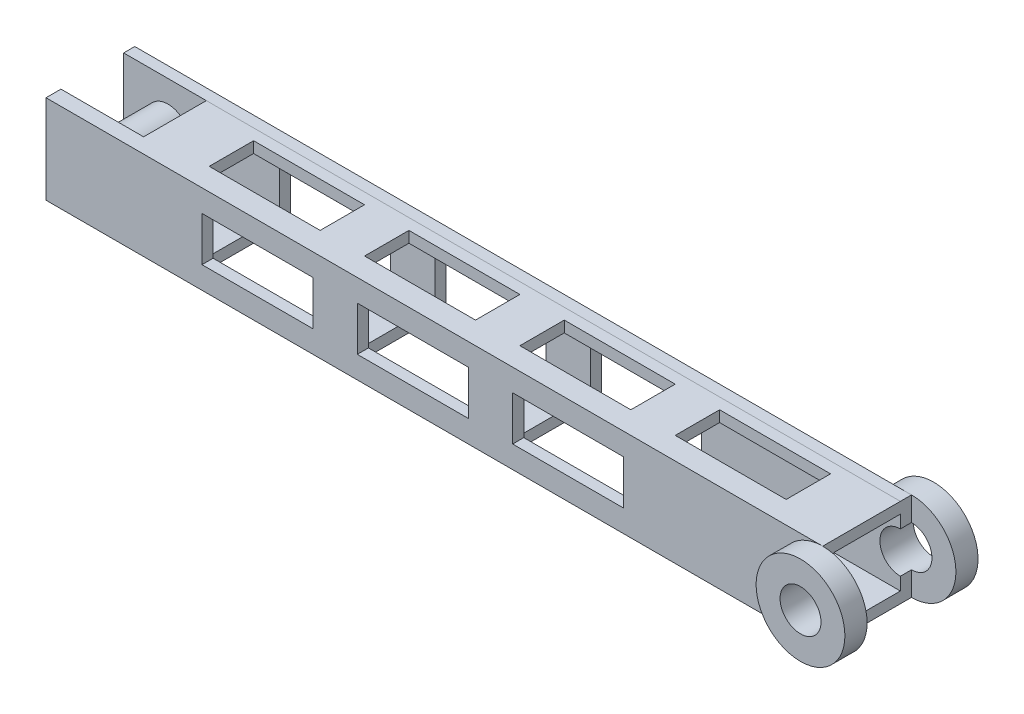
SolidWorks part; units mm, degrees
material "ENPH 253 Hardboard"
ref_plane "Front Plane" through (0, 0, 0) normal (0, 0, 1) x (1, 0, 0)
ref_plane "Top Plane" through (0, 0, 0) normal (0, 1, 0) x (1, 0, 0)
ref_plane "Right Plane" through (0, 0, 0) normal (1, 0, 0) x (0, 0, -1)
sketch "Sketch1" plane through (0, 0, 0) normal (0, 0, 1) x (1, 0, 0)
  line L1 (-109.1179, 29.5837) -> (240.8821, 29.5837)
  line L2 (-109.1179, 29.5837) -> (-109.1179, -10.4163)
  line L3 (-109.1179, -10.4163) -> (240.8821, -10.4163)
  line L4 (240.8821, 29.5837) -> (240.8821, -10.4163)
  dimension "D1" = 350
  dimension "D2" = 40
extrude "Boss-Extrude1" add sketch "Sketch1" along normal blind 5
sketch "Sketch2" plane through (0, 0, 5) normal (0, 0, 1) x (1, 0, 0)
  line L0 (-109.1179, 29.5837) -> (-109.1179, -10.4163) construction
  line L1 (-109.1179, 29.5849) -> (240.8821, 29.5849)
  line L2 (-109.1179, 29.5849) -> (-109.1179, 24.5849)
  line L3 (-109.1179, 24.5849) -> (240.8821, 24.5849)
  line L4 (240.8821, 29.5849) -> (240.8821, 24.5849)
  line L5 (240.8821, -10.4163) -> (240.8821, 29.5837) construction
  line L7 (-109.1179, -5.4163) -> (240.8821, -5.4163)
  line L8 (-109.1179, -5.4163) -> (-109.1179, -10.4163)
  line L9 (-109.1179, -10.4163) -> (240.8821, -10.4163)
  line L10 (240.8821, -5.4163) -> (240.8821, -10.4163)
  dimension "D1" = 5
  dimension "D2" = 5
extrude "Boss-Extrude2" add sketch "Sketch2" along normal blind 30 contours L2 L1 L4 L3
sketch "Sketch3" plane through (0, 0, 5) normal (0, 0, 1) x (1, 0, 0)
  line L0 (-109.1179, 24.5849) -> (-109.1179, -10.4163) construction
  line L1 (-109.1179, -5.4163) -> (240.8821, -5.4163)
  line L2 (-109.1179, -5.4163) -> (-109.1179, -10.4163)
  line L3 (-109.1179, -10.4163) -> (240.8821, -10.4163)
  line L4 (240.8821, -5.4163) -> (240.8821, -10.4163)
  dimension "D1" = 5
extrude "Boss-Extrude3" add sketch "Sketch3" along normal blind 30
sketch "Sketch5" plane through (0, 0, 35) normal (0, 0, 1) x (1, 0, 0)
  line L1 (-109.1179, 29.5849) -> (240.8821, 29.5849)
  line L2 (-109.1179, 29.5849) -> (-109.1179, -10.4163)
  line L3 (-109.1179, -10.4163) -> (240.8821, -10.4163)
  line L4 (240.8821, 29.5849) -> (240.8821, -10.4163)
extrude "Boss-Extrude4" add sketch "Sketch5" along normal blind 5
sketch "Sketch7" plane through (0, 0, 40) normal (0, 0, 1) x (1, 0, 0)
  line L0 (-109.1179, -10.4163) -> (240.8821, -10.4163) construction
  line L1 (-38.8282, 19.5837) -> (11.1718, 19.5837)
  line L2 (-38.8282, 19.5837) -> (-38.8282, -0.4163)
  line L3 (-38.8282, -0.4163) -> (11.1718, -0.4163)
  line L4 (11.1718, 19.5837) -> (11.1718, -0.4163)
  line L5 (31.1718, 19.5837) -> (81.1718, 19.5837)
  line L6 (31.1718, 19.5837) -> (31.1718, -0.4163)
  line L7 (31.1718, -0.4163) -> (81.1718, -0.4163)
  line L8 (81.1718, 19.5837) -> (81.1718, -0.4163)
  line L9 (101.1718, 19.5837) -> (151.1718, 19.5837)
  line L10 (101.1718, 19.5837) -> (101.1718, -0.4163)
  line L11 (101.1718, -0.4163) -> (151.1718, -0.4163)
  line L12 (151.1718, 19.5837) -> (151.1718, -0.4163)
  line L13 (240.8821, 29.5837) -> (-109.1179, 29.5837) construction
  dimension "D1" = 10
  dimension "D2" = 10
  dimension "D3" = 10
  dimension "D4" = 10
  dimension "D5" = 10
  dimension "D6" = 10
  dimension "D7" = 50
  dimension "5cm" = 50
  dimension "D8" = 50
  dimension "D9" = 20
  dimension "D10" = 20
extrude "Cut-Extrude1" cut sketch "Sketch7" against normal through all both and the other way through all
sketch "Sketch8" plane through (0, 29.5849, 0) normal (0, 1, 0) x (1, 0, 0)
  line L0 (-109.1179, -40) -> (240.8821, -40) construction
  line L1 (-45.5754, -30) -> (4.4246, -30)
  line L2 (-45.5754, -30) -> (-45.5754, -10)
  line L3 (-45.5754, -10) -> (4.4246, -10)
  line L4 (4.4246, -30) -> (4.4246, -10)
  line L5 (24.4246, -30) -> (74.4246, -30)
  line L6 (24.4246, -30) -> (24.4246, -10)
  line L7 (24.4246, -10) -> (74.4246, -10)
  line L8 (74.4246, -30) -> (74.4246, -10)
  line L9 (94.4246, -30) -> (144.4246, -30)
  line L10 (94.4246, -30) -> (94.4246, -10)
  line L11 (94.4246, -10) -> (144.4246, -10)
  line L12 (144.4246, -30) -> (144.4246, -10)
  line L13 (164.4246, -30) -> (214.4246, -30)
  line L14 (164.4246, -30) -> (164.4246, -10)
  line L15 (164.4246, -10) -> (214.4246, -10)
  line L16 (214.4246, -30) -> (214.4246, -10)
  line L17 (-109.1179, 0) -> (240.8821, 0) construction
  dimension "D1" = 10
  dimension "D2" = 10
  dimension "D3" = 50
  dimension "D4" = 10
  dimension "D5" = 10
  dimension "D6" = 10
  dimension "D7" = 10
  dimension "D8" = 10
  dimension "D9" = 10
  dimension "D10" = 50
  dimension "D11" = 50
  dimension "D12" = 50
  dimension "D13" = 20
  dimension "D14" = 20
  dimension "D15" = 20
extrude "Cut-Extrude2" cut sketch "Sketch8" against normal through all both and the other way through all
sketch "Sketch9" plane through (0, 0, 40) normal (0, 0, 1) x (1, 0, 0)
  line L0 (240.8821, -10.4163) -> (240.8821, 29.5849) construction
  circle A0 centre (240.8821, 9.5843) radius 20
extrude "Boss-Extrude5" add sketch "Sketch9" along normal blind 10
sketch "Sketch10" plane through (0, 0, 0) normal (0, 0, -1) x (-1, 0, 0)
  line L0 (-240.8821, -10.4157) -> (-240.8821, 29.5843) construction
  circle A0 centre (-240.8821, 9.5843) radius 20
extrude "Boss-Extrude6" add sketch "Sketch10" along normal blind 10
sketch "Sketch11" plane through (0, 29.5849, 0) normal (0, 1, 0) x (1, 0, 0)
  line L0 (-109.1179, -40) -> (-109.1179, -5) construction
  line L1 (-109.1179, -33.2634) -> (-71.8639, -33.2634)
  line L2 (-109.1179, -33.2634) -> (-109.1179, -5)
  line L3 (-109.1179, -5) -> (-71.8639, -5)
  line L4 (-71.8639, -33.2634) -> (-71.8639, -5)
extrude "Cut-Extrude3" cut sketch "Sketch11" against normal through all
sketch "Sketch12" plane through (0, 0, 50) normal (0, 0, 1) x (1, 0, 0)
  circle A0 centre (240.8821, 9.5843) radius 9.2248
  circle A1 centre (240.8821, 9.5843) radius 20 construction
  dimension "D1" = 0
extrude "Cut-Extrude4" cut sketch "Sketch12" against normal through all both and the other way through all
sketch "Sketch13" plane through (0, 0, 40) normal (0, 0, 1) x (1, 0, 0)
  line L0 (-109.1179, -10.4163) -> (240.8821, -10.4163) construction
  line L1 (-109.1179, 29.5849) -> (-109.1179, -10.4163) construction
  circle A0 centre (-89.1179, 9.5837) radius 10
  dimension "D1" = 20
  dimension "D2" = 20
extrude "Boss-Extrude7" add sketch "Sketch13" against normal blind 40
